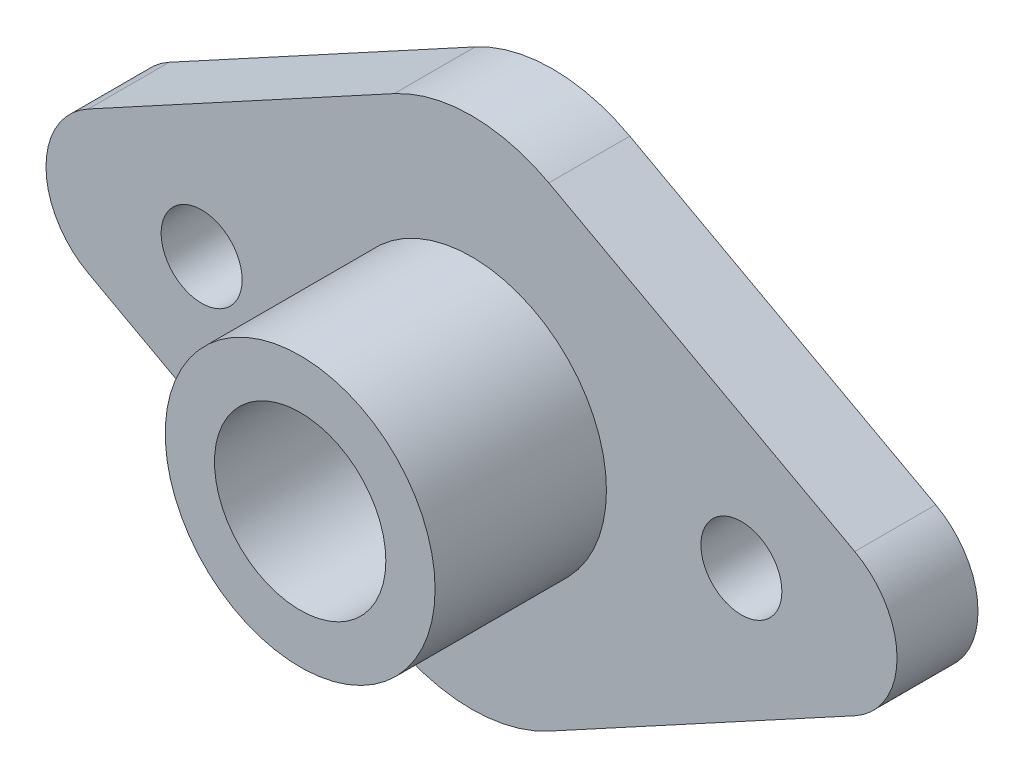
SolidWorks part; units mm, degrees
ref_plane "Front Plane" through (0, 0, 0) normal (0, 0, 1) x (1, 0, 0)
ref_plane "Top Plane" through (0, 0, 0) normal (0, 1, 0) x (1, 0, 0)
ref_plane "Right Plane" through (0, 0, 0) normal (1, 0, 0) x (0, 0, -1)
sketch "Sketch1" plane through (0, 0, 0) normal (0, 0, 1) x (1, 0, 0)
  line L0 (0, 9.525) -> (0, -9.525) construction
  line L1 (-19.05, 0) -> (19.05, 0) construction
  line L2 (-2.8652, 8.7967) -> (-14.2004, 2.6358)
  line L3 (2.8652, 8.7967) -> (14.2004, 2.6358)
  line L4 (-2.8652, 8.7967) -> (-19.05, 0)
  line L5 (2.8652, 8.7967) -> (19.05, 0)
  line L6 (-2.8652, -8.7967) -> (-14.2004, -2.6358)
  line L7 (2.8652, -8.7967) -> (14.2004, -2.6358)
  arc A0 (-2.8652, 8.7967) -> (2.8652, 8.7967) centre (0, 3.525) cw
  arc A1 (-2.8652, -8.7967) -> (2.8652, -8.7967) centre (0, -3.525) ccw
  arc A2 (14.2004, 2.6358) -> (14.2004, -2.6358) centre (12.7678, 0) cw
  arc A3 (-14.2004, 2.6358) -> (-14.2004, -2.6358) centre (-12.7678, 0) ccw
  circle A4 centre (0, 0) radius 3.175
  circle A5 centre (10, 0) radius 1.5
  circle A7 centre (-10, 0) radius 1.5
  point P5 (0, 9.525)
  point P7 (0, 0)
  point P8 (0, 0)
  dimension "D3" = 6
  dimension "D4" = 3
  dimension "D5" = 6.35
  dimension "D6" = 3
  dimension "D1" = 38.1
  dimension "D2" = 19.05
  dimension "D7" = 10
extrude "Boss-Extrude1" add sketch "Sketch1" along normal blind 3 contours L2 A3 L6 A1 L7 A2 L3 A0
sketch "Sketch2" plane through (0, 0, 3) normal (0, 0, 1) x (1, 0, 0)
  circle A0 centre (0, 0) radius 5
  circle A1 centre (0, 0) radius 3.175
  dimension "D1" = 10
extrude "Boss-Extrude2" add sketch "Sketch2" along normal blind 6.35
